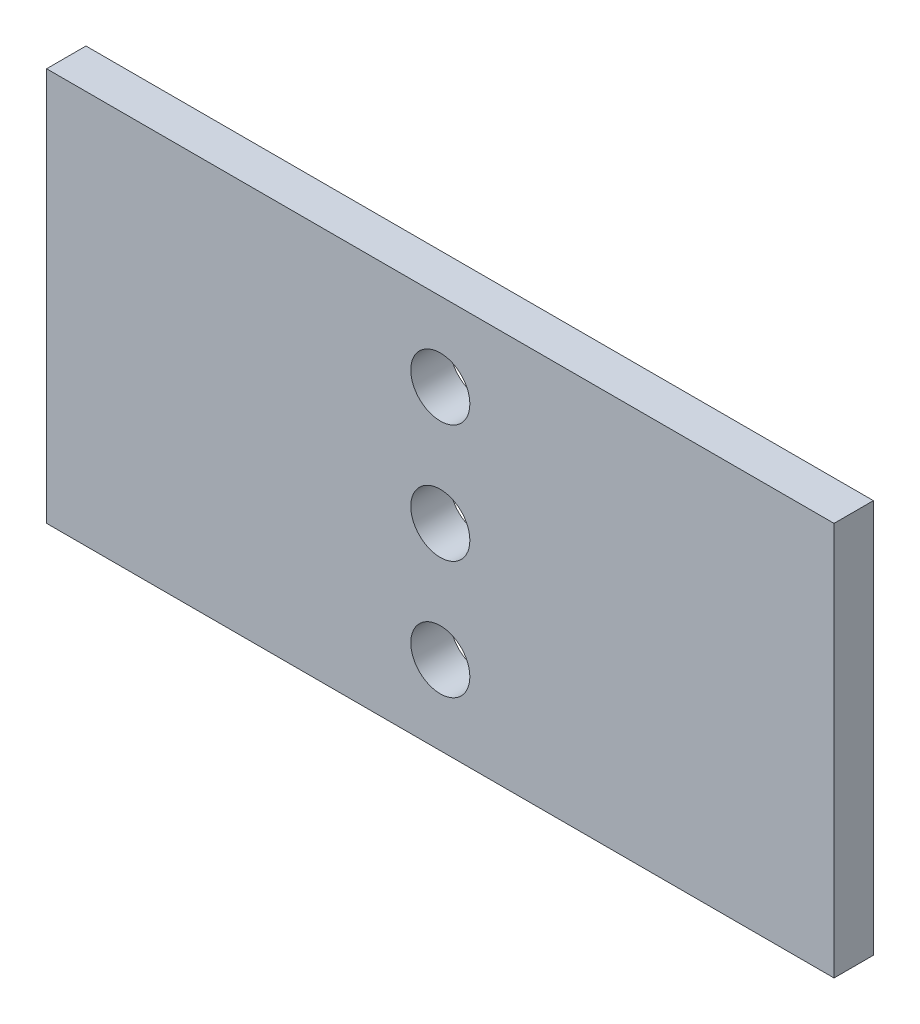
SolidWorks part; units mm, degrees
material "1023 Carbon Steel Sheet (SS)"
ref_plane "Front Plane" through (0, 0, 0) normal (0, 0, 1) x (1, 0, 0)
ref_plane "Top Plane" through (0, 0, 0) normal (0, 1, 0) x (1, 0, 0)
ref_plane "Right Plane" through (0, 0, 0) normal (1, 0, 0) x (0, 0, -1)
sketch "Sketch1" plane through (0, 0, 0) normal (0, 0, 1) x (1, 0, 0)
  line L1 (-100, -50) -> (100, -50)
  line L2 (-100, -50) -> (-100, 50)
  line L3 (-100, 50) -> (100, 50)
  line L4 (100, -50) -> (100, 50)
  line L5 (-100, -50) -> (100, 50) construction
  line L6 (-100, 50) -> (100, -50) construction
  circle A0 centre (0, 0) radius 7.5
  circle A1 centre (0, 30) radius 7.5
  circle A2 centre (0, -30) radius 7.5
  point P0 (0, 0)
  dimension "D3" = 15
  dimension "D4" = 15
  dimension "D5" = 15
  dimension "D1" = 200
  dimension "D2" = 100
  dimension "D6" = 30
  dimension "D7" = 30
extrude "Boss-Extrude1" add sketch "Sketch1" along normal blind 10
